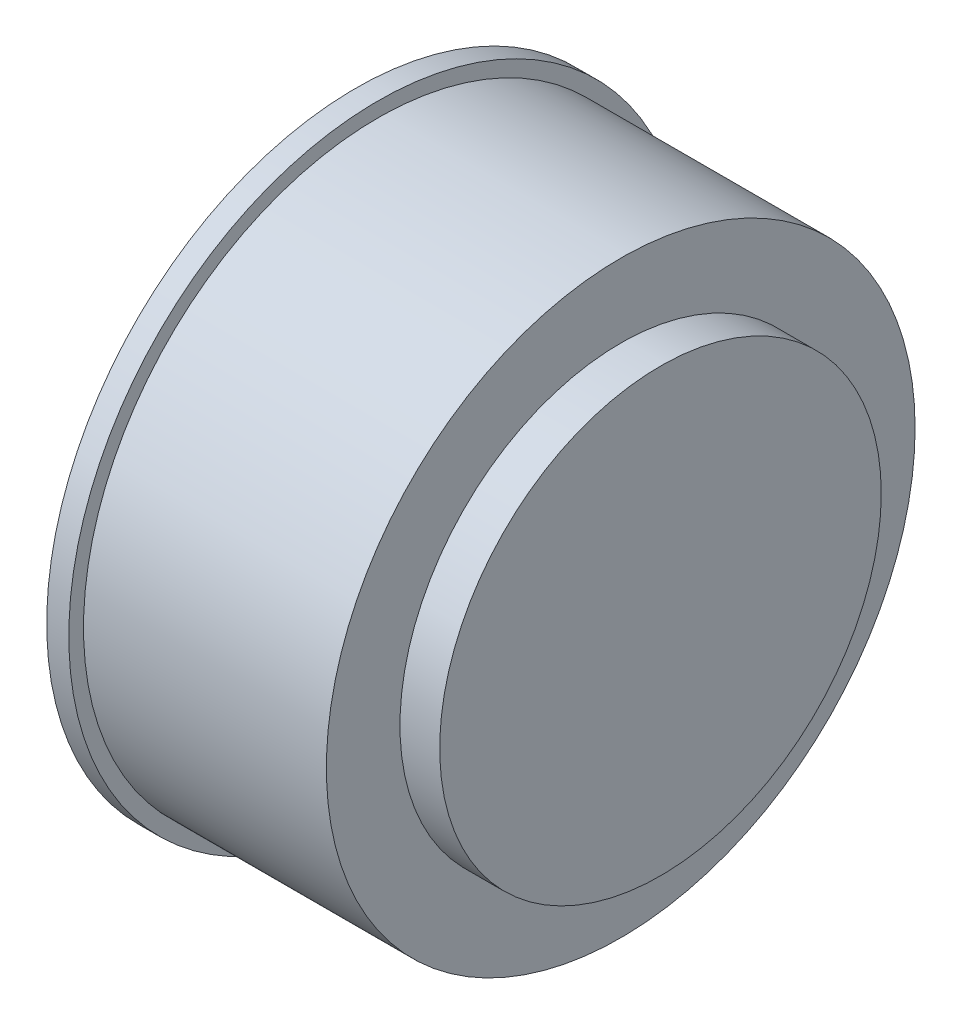
SolidWorks part; units mm, degrees
ref_plane "Front Plane" through (0, 0, 0) normal (0, 0, 1) x (1, 0, 0)
ref_plane "Top Plane" through (0, 0, 0) normal (0, 1, 0) x (1, 0, 0)
ref_plane "Right Plane" through (0, 0, 0) normal (1, 0, 0) x (0, 0, -1)
sketch "Sketch2" plane through (0, 0, 0) normal (0, 1, 0) x (1, 0, 0)
  line L0 (0, 0) -> (0, 15)
  line L1 (0, 15) -> (-2.7, 15)
  line L2 (-2.7, 15) -> (-2.7, 20)
  line L3 (-2.7, 20) -> (-19.2, 20)
  line L4 (-19.2, 20) -> (-19.2, 21)
  line L5 (-19.2, 21) -> (-20.7, 21)
  line L6 (-20.7, 21) -> (-20.7, 17.6528)
  line L7 (0, 0) -> (-41.2311, 0) construction
  line L11 (-20.7, 14.5) -> (-20.7, 8)
  line L12 (-20.7, 8) -> (-15.7, 8)
  line L13 (-15.7, 8) -> (-15.7, 6)
  line L14 (-15.7, 6) -> (-14.7, 6)
  line L15 (-14.7, 6) -> (-14.7, 0)
  line L16 (-14.7, 0) -> (0, 0)
  line L17 (-20.7, 17.6528) -> (-20.7, 14.5)
  dimension "D1" = 15
  dimension "D2" = 2.7
  dimension "D3" = 5
  dimension "D4" = 16.5
  dimension "D5" = 1
  dimension "D6" = 1.5
  dimension "D8" = 8
  dimension "D9" = 6
  dimension "D10" = 5
  dimension "D13" = 1
revolve "Revolve1" add sketch "Sketch2" angle 360 about L7
sketch "Sketch3" plane through (-20.7, 0, 0) normal (-1, 0, 0) x (0, 0, 1)
  circle A0 centre (0, 16) radius 1.5
  circle A1 centre (13.8564, 7.9047) radius 1.5
  circle A2 centre (13.7739, -8.1429) radius 1.5
  circle A3 centre (-0.165, -16.0953) radius 1.5
  circle A4 centre (-14.0214, -8) radius 1.5
  circle A5 centre (-13.9389, 8.0476) radius 1.5
  point P2 (0, 0)
  point P3 (0, 0)
  point P4 (0, 0)
  point P17 (0, 0)
  dimension "D1" = 3
  dimension "D3" = 16
  dimension "D2" = 6
extrude "Cut-Extrude1" cut sketch "Sketch3" against normal blind 4
